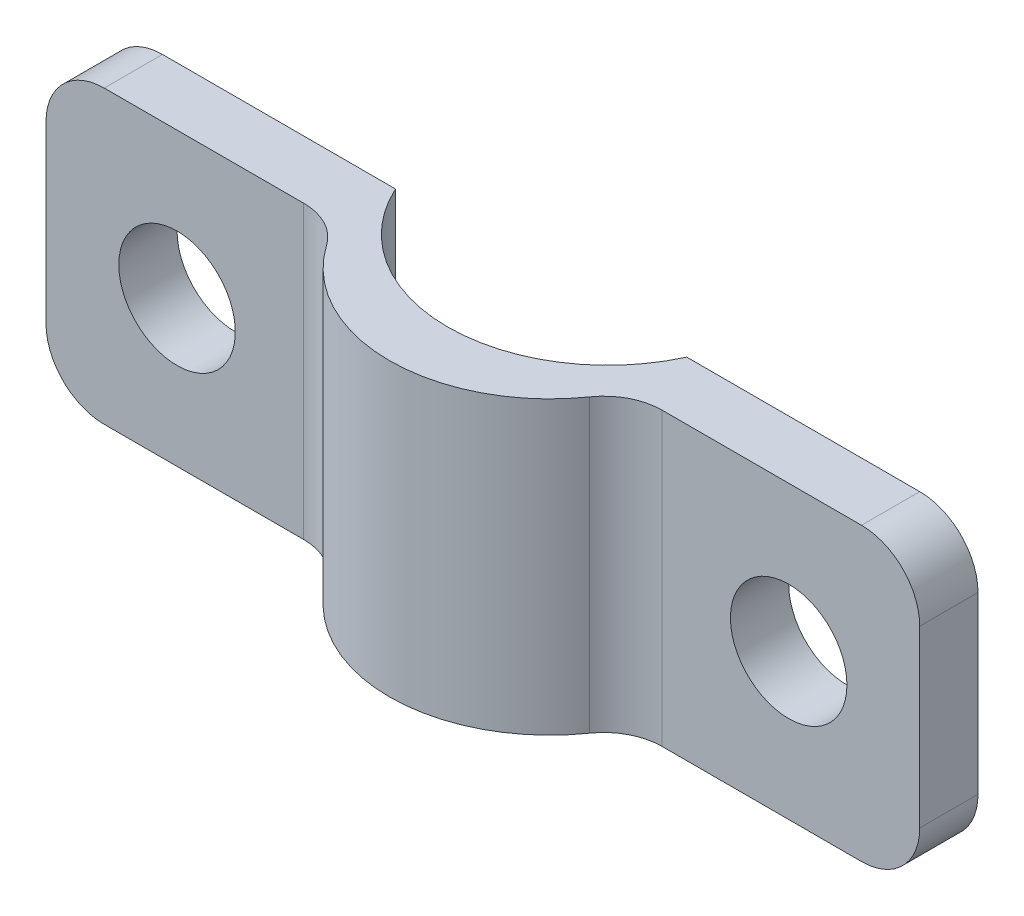
SolidWorks part; units mm, degrees
material "6061-T4 (SS)"
ref_plane "Front Plane" through (0, 0, 0) normal (0, 0, 1) x (1, 0, 0)
ref_plane "Top Plane" through (0, 0, 0) normal (0, 1, 0) x (1, 0, 0)
ref_plane "Right Plane" through (0, 0, 0) normal (1, 0, 0) x (0, 0, -1)
sketch "Sketch1" plane through (0, 0, 0) normal (0, 1, 0) x (1, 0, 0)
  line L0 (0, 5.921) -> (0, -6.5769) construction
  line L1 (-7.7775, 0) -> (9.4876, 0) construction
  line L2 (-15, 0) -> (-5, 0) construction
  line L3 (-15, 0) -> (-15, -2)
  line L4 (-15, -2) -> (-5, -2)
  line L5 (-5, 0) -> (-15, 0)
  line L6 (15, 0) -> (5, 0) construction
  line L7 (5, 0) -> (15, 0)
  line L8 (15, -2) -> (5, -2)
  line L9 (15, 0) -> (15, -2)
  arc A0 (-5, 0) -> (5, 0) centre (0, 2.2913) ccw
  arc A1 (-5, -2) -> (5, -2) centre (0, 0.2913) ccw
  dimension "D1" = 5.5
  dimension "D2" = 5.5
  dimension "D3" = 2
  dimension "D4" = 10
  dimension "D5" = 10
extrude "Boss-Extrude1" add sketch "Sketch1" along normal blind 10 separate body contours L4 A1 L8 L9 L7 A0 L5 L3
fillet "Fillet1" radius 2 2 edges at (5, 5, 2) (-5, 5, 2)
fillet "Fillet2" radius 2 4 edges at (15, 10, 1) (15, 0, 1) (-15, 0, 1) (-15, 10, 1)
sketch "Sketch2" plane through (0, 0, 0) normal (0, 0, 1) x (1, 0, 0)
  line L0 (0, 13.5295) -> (0, -1.337) construction
  line L1 (-16.5204, 5) -> (17.6166, 5) construction
  line L2 (-10.5, 13.5295) -> (-10.5, -2.0101) construction
  line L3 (-15, 8) -> (-15, 2) construction
  point P9 (-10.5, 5)
  point P12 (10.5, 5)
  dimension "D1" = 5
  dimension "D2" = 4.5
hole_wizard "Ø4.0mm Dowel Hole1" positions "Sketch2" profile "Sketch3" hole size "Ø4.0" standard "ANSI Metric" end condition through all
sketch "Sketch3" plane through (10.5, 5, 0) normal (1, 0, 0) x (0, 1, 0)
  line L0 (0, 0) -> (0, 5.2087)
  line L1 (0, 5.2087) -> (2, 5.2087)
  line L2 (2, 5.2087) -> (2, 0)
  line L5 (2, 0) -> (0, 0)
  line L11 (0, -6.35) -> (0, 107.95) construction
  dimension "Thru Hole Dia." = 4
  dimension "Thru Hole Depth" = 5.2087
